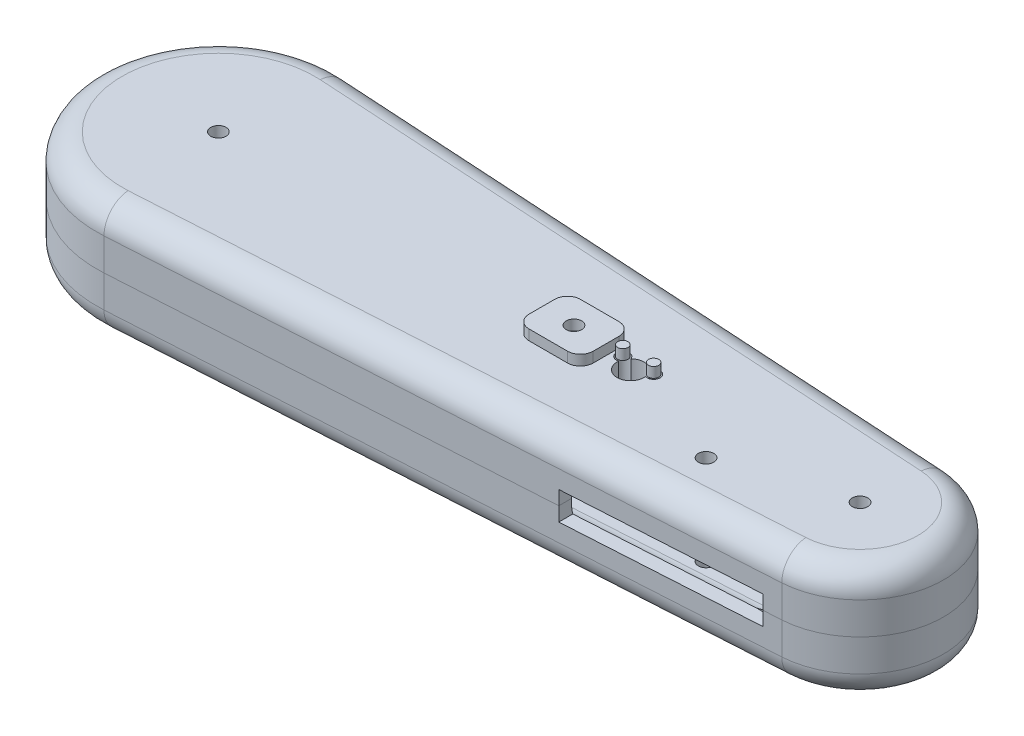
SolidWorks part; units mm, degrees
material "ABS PC"
ref_plane "Alzado" through (0, 0, 0) normal (1, 0, 0) x (0, 1, 0)
ref_plane "Planta" through (0, 0, 0) normal (0, 0, 1) x (0, 1, 0)
ref_plane "Vista lateral" through (0, 0, 0) normal (0, 1, 0) x (-1, 0, 0)
sketch "Croquis1" plane through (0, 0, 0) normal (0, 1, 0) x (-1, 0, 0)
  line L0 (0, 0) -> (250, 0) construction
  line L1 (-1.95, 32.4414) -> (247.15, 47.4144)
  line L2 (-1.95, -32.4414) -> (247.15, -47.4144)
  circle A0 centre (0, 0) radius 3
  circle A1 centre (250, 0) radius 3
  arc A2 (-1.95, 32.4414) -> (-1.95, -32.4414) centre (0, 0) ccw
  arc A3 (247.15, -47.4144) -> (247.15, 47.4144) centre (250, 0) ccw
  circle A4 centre (45, 15) radius 3
  dimension "D2" = 6
  dimension "D3" = 65
  dimension "D4" = 95
  dimension "D1" = 250
  dimension "D5" = 45
  dimension "D6" = 15
extrude "Saliente-Extruir1" add sketch "Croquis1" along normal mid plane 45
sketch "Croquis2" plane through (0, 0, 0) normal (0, 1, 0) x (-1, 0, 0)
  line L0 (-1.65, -27.4505) -> (247.45, -42.4234)
  line L1 (247.45, 42.4234) -> (-1.65, 27.4505)
  line L2 (-1.95, -32.4414) -> (247.15, -47.4144)
  line L3 (247.15, 47.4144) -> (-1.95, 32.4414)
  line L4 (-1.95, -32.4414) -> (247.15, -47.4144) construction
  line L5 (247.15, 47.4144) -> (-1.95, 32.4414) construction
  line L6 (0, 0) -> (250, 0) construction
  arc A0 (-1.65, 27.4505) -> (-1.65, -27.4505) centre (0, 0) ccw
  arc A1 (247.45, -42.4234) -> (247.45, 42.4234) centre (250, 0) ccw
  arc A2 (-1.95, 32.4414) -> (-1.95, -32.4414) centre (0, 0) ccw
  arc A3 (247.15, -47.4144) -> (247.15, 47.4144) centre (250, 0) ccw
  arc A4 (-1.95, 32.4414) -> (-1.95, -32.4414) centre (0, 0) ccw construction
  arc A5 (247.15, -47.4144) -> (247.15, 47.4144) centre (250, 0) ccw construction
  circle A6 centre (190, 0) radius 5
  circle A7 centre (25, 0) radius 5
  dimension "D3" = 10
  dimension "D4" = 60
  dimension "D5" = 25
  dimension "D1" = 0
  dimension "D2" = 5
extrude "Cortar-Extruir1" cut sketch "Croquis2" along normal offset from surface 10 and the other way offset from surface (12.5 mm away) 10 up to face at (-250, 22.5, 3) other way up to face at (-127.55, -22.5, 0)
split "Partir1" trim tools "Vista lateral" bodies to split 105 resulting bodies 107 108
fillet "Redondeo4" radius 10 8 edges at (-297.5, 22.5, 0) (-122.6, 22.5, -39.9279) (32.5, 22.5, 0) (-122.6, 22.5, 39.9279) (27.5, 12.5, 0) (-122.9, 12.5, 34.9369) (-292.5, 12.5, 0) (-122.9, 12.5, -34.9369)
fillet "Redondeo5" radius 10 8 edges at (-297.5, -22.5, 0) (-122.6, -22.5, -39.9279) (32.5, -22.5, 0) (-122.6, -22.5, 39.9279) (-292.5, -12.5, 0) (-122.9, -12.5, 34.9369) (27.5, -12.5, 0) (-122.9, -12.5, -34.9369)
sketch "Croquis4" plane through (0, 0, 0) normal (0, 1, 0) x (-1, 0, 0)
  line L0 (-1.95, 32.4414) -> (247.15, 47.4144) construction
  line L1 (80, 37.3673) -> (5, 37.3673)
  line L2 (80, 37.3673) -> (80, 27.8502)
  line L3 (80, 27.8502) -> (5, 27.8502)
  line L4 (5, 37.3673) -> (5, 27.8502)
  line L5 (247.45, 42.4234) -> (-1.65, 27.4505) construction
  circle A0 centre (45, 15) radius 3 construction
  circle A1 centre (45, 15) radius 3 construction
  dimension "D1" = 40
  dimension "D2" = 35
extrude "Cortar-Extruir2" cut sketch "Croquis4" against normal mid plane 11
sketch "Croquis5" plane through (0, 22.5, 0) normal (0, 1, 0) x (-1, 0, 0)
  line L0 (250, 0) -> (111.457, 0) construction
  circle A0 centre (111.457, 0) radius 3
  circle A1 centre (176.457, 15) radius 3
  dimension "D2" = 6
  dimension "D3" = 65
  dimension "D5" = 6
  dimension "D1" = 138.543
  dimension "D4" = 15
extrude "Cortar-Extruir3" cut sketch "Croquis5" against normal through all both and the other way through all
sketch "Croquis6" plane through (0, 22.5, 0) normal (0, 1, 0) x (-1, 0, 0)
  line L0 (89.4249, 0) -> (89.4249, 27.9158) construction
  line L1 (247.75, 37.4324) -> (-1.35, 22.4595) construction
  line L2 (83.4249, -3) -> (95.4249, -3) construction
  arc A0 (85.7957, -3.7935) -> (93.0542, -3.7935) centre (89.4249, 0) ccw
  arc A1 (84.2125, -0.6273) -> (85.7957, -3.7935) centre (83.4249, -3) ccw
  arc A2 (93.0542, -3.7935) -> (94.6373, -0.6273) centre (95.4249, -3) ccw
  arc A3 (94.6373, -0.6273) -> (84.2125, -0.6273) centre (89.4249, 0) ccw
  dimension "D1" = 10.5
  dimension "D3" = 5
  dimension "D2" = 3
  dimension "D4" = 12
extrude "Cortar-Extruir4" cut sketch "Croquis6" against normal up to next (10 mm away) and the other way through all
sketch "Croquis8" plane through (0, 22.5, 0) normal (0, 1, 0) x (-1, 0, 0)
  line L1 (103.957, -10) -> (118.957, -10)
  line L2 (98.957, -5) -> (98.957, 5)
  line L3 (103.957, 10) -> (118.957, 10)
  line L4 (123.957, -5) -> (123.957, 5)
  line L5 (98.957, -10) -> (123.957, 10) construction
  line L6 (98.957, 10) -> (123.957, -10) construction
  arc A0 (118.957, -10) -> (123.957, -5) centre (118.957, -5) ccw
  arc A1 (118.957, 10) -> (123.957, 5) centre (118.957, 5) cw
  arc A2 (103.957, -10) -> (98.957, -5) centre (103.957, -5) cw
  arc A3 (98.957, 5) -> (103.957, 10) centre (103.957, 5) cw
  circle A4 centre (111.457, 0) radius 3
  circle A5 centre (83.4249, -3) radius 2
  circle A6 centre (95.4249, -3) radius 2
  circle A7 centre (111.457, 0) radius 3 construction
  point P0 (111.457, 0)
  dimension "D1" = 5
  dimension "D4" = 4
  dimension "D2" = 25
  dimension "D3" = 20
extrude "Saliente-Extruir2" add sketch "Croquis8" along normal blind 4 separate body
equation "\"L1\"= 250"
equation "\"agujeros\"= 6"
equation "\"ancho_total\"= 45"
equation "\"esp\"= 10"
equation "\"D1@Croquis1\"=\"L1\""
equation "\"D2@Croquis1\"=\"agujeros\""
equation "\"deje1\"= 65"
equation "\"deje2\"= 95"
equation "\"D3@Croquis1\"=\"deje1\""
equation "\"D4@Croquis1\"=\"deje2\""
equation "\"D1@Saliente-Extruir1\"=\"ancho_total\""
equation "\"D1@Cortar-Extruir1\"=\"esp\""
equation "\"D2@Cortar-Extruir1\"=\"esp\""
equation "\"D1@Cortar-Extruir2\"=\"esp\"+1"
equation "\"distancia_centros_poleas\"=138.543"
equation "\"D1@Croquis5\"=\"distancia_centros_poleas\""
equation "\"D2@Croquis5\"=\"agujeros\""
equation "\"D5@Croquis5\"=\"D2@Croquis5\""
equation "\"distancia_ejes_torn_motor\"=12"
equation "\"D4@Croquis6\"=\"distancia_ejes_torn_motor\""
